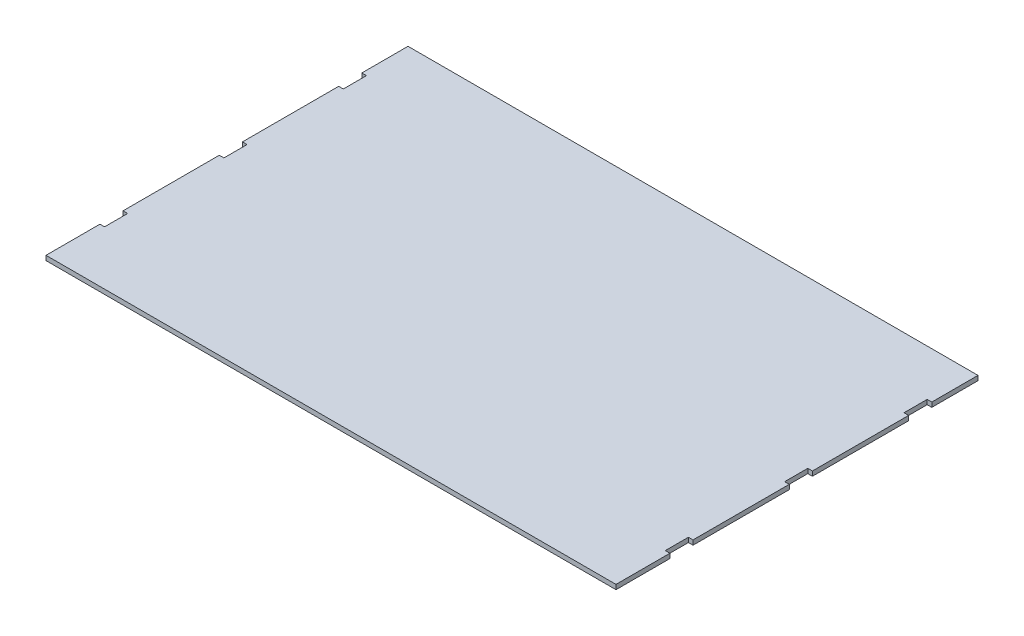
SolidWorks part; units mm, degrees
ref_plane "Front Plane" through (0, 0, 0) normal (0, 0, 1) x (1, 0, 0)
ref_plane "Top Plane" through (0, 0, 0) normal (0, 1, 0) x (1, 0, 0)
ref_plane "Right Plane" through (0, 0, 0) normal (1, 0, 0) x (0, 0, -1)
sketch "Sketch16" plane through (0, 0, 0) normal (0, 1, 0) x (1, 0, 0)
  line L0 (370, 205) -> (367, 205)
  line L1 (0, 0) -> (370, 0)
  line L2 (0, 0) -> (0, 35)
  line L3 (0, 235) -> (370, 235)
  line L7 (370, 127.5) -> (367, 127.5)
  line L8 (367, 127.5) -> (367, 112.5)
  line L9 (367, 112.5) -> (370, 112.5)
  line L10 (370, 235) -> (370, 205)
  line L11 (370, 112.5) -> (370, 50)
  line L12 (367, 205) -> (367, 190)
  line L13 (367, 190) -> (370, 190)
  line L14 (370, 190) -> (370, 127.5)
  line L15 (367, 50) -> (370, 50)
  line L16 (367, 35) -> (367, 50)
  line L17 (370, 35) -> (367, 35)
  line L18 (370, 35) -> (370, 0)
  line L19 (0, 35) -> (3, 35)
  line L20 (3, 35) -> (3, 50)
  line L21 (3, 50) -> (0, 50)
  line L22 (3, 190) -> (0, 190)
  line L23 (3, 205) -> (3, 190)
  line L24 (3, 112.5) -> (0, 112.5)
  line L25 (3, 127.5) -> (3, 112.5)
  line L26 (0, 127.5) -> (3, 127.5)
  line L27 (0, 205) -> (3, 205)
  line L28 (0, 50) -> (0, 112.5)
  line L29 (0, 127.5) -> (0, 190)
  line L30 (0, 205) -> (0, 235)
  dimension "D1" = 370
  dimension "D2" = 235
  dimension "D3" = 3
  dimension "D4" = 15
  dimension "D5" = 3
  dimension "D6" = 30
extrude "Boss-Extrude1" add sketch "Sketch16" along normal blind 3
